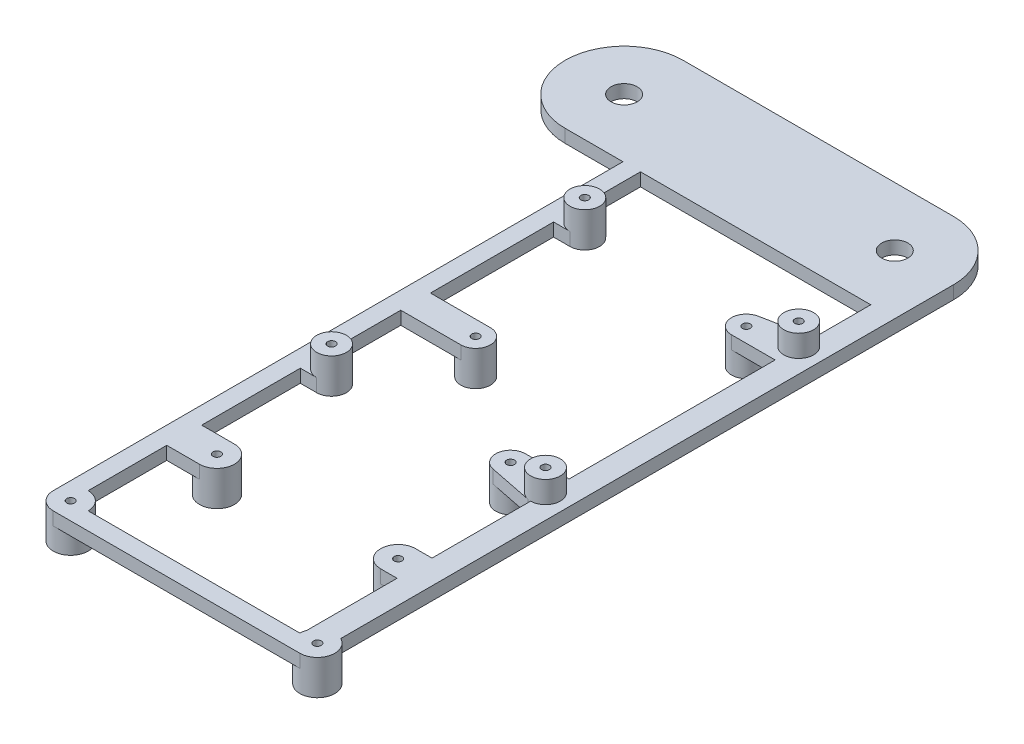
SolidWorks part; units mm, degrees
ref_plane "Front Plane" through (0, 0, 0) normal (0, 0, 1) x (1, 0, 0)
ref_plane "Top Plane" through (0, 0, 0) normal (0, 1, 0) x (1, 0, 0)
ref_plane "Right Plane" through (0, 0, 0) normal (1, 0, 0) x (0, 0, -1)
ref_plane "SHIFTER SCREW HOLE MOUNT PLANE" through (0, -50.5, 0) normal (0, 1, 0) x (1, 0, 0)
sketch "SHIFTER SCREW HOLE LOCATIONS" plane through (0, -50.5, 0) normal (0, 1, 0) x (1, 0, 0)
  point P0 (12, 93)
  point P1 (-50, 93)
sketch "Sketch2" plane through (0, -50.5, 0) normal (0, 1, 0) x (1, 0, 0)
  line L0 (-50, 93) -> (12, 93) construction
  line L1 (-50, 106.5) -> (12, 106.5)
  line L2 (-50, 79.5) -> (12, 79.5)
  arc A0 (-50, 106.5) -> (-50, 79.5) centre (-50, 93) ccw
  arc A1 (12, 79.5) -> (12, 106.5) centre (12, 93) ccw
  circle A2 centre (-50, 93) radius 3
  circle A3 centre (12, 93) radius 3
  point P4 (-19, 93)
  point P15 (0, 0)
  point P16 (0, 0)
  point P17 (0, 0)
  dimension "D1" = 13.5
  dimension "D2" = 6
extrude "SHIFTER HOLE IF" add sketch "Sketch2" against normal blind 3
sketch "Sketch3" plane through (0, -50.5, 0) normal (0, 1, 0) x (1, 0, 0)
  line L1 (-29, 63) -> (20, 63) construction
  line L2 (-29, 63) -> (-29, 5) construction
  line L3 (-29, 5) -> (20, 5) construction
  line L4 (20, 63) -> (20, 5) construction
  circle A0 centre (-29, 63) radius 0.9
  circle A1 centre (20, 63) radius 0.9
  circle A2 centre (20, 5) radius 0.9
  circle A3 centre (-29, 5) radius 0.9
  circle A4 centre (-29, 63) radius 3.4
  circle A5 centre (20, 63) radius 3.4
  circle A6 centre (20, 5) radius 3.4
  circle A7 centre (-29, 5) radius 3.4
  point P1 (10.7793, 10)
  point P16 (-8.0489, -3.7251)
  point P18 (-3.7899, 3.2614)
  dimension "D1" = 1.8
  dimension "D2" = 49
  dimension "D3" = 58
  dimension "D5" = 20
  dimension "D6" = 5
  dimension "D4" = 2.5
extrude "RPI4 SCREW BOSSES" add sketch "Sketch3" along normal blind 5 and the other way blind 3 separate body
sketch "Sketch4" plane through (0, -50.5, 0) normal (0, 1, 0) x (1, 0, 0)
  line L0 (10, 61) -> (10, 7) construction
  line L1 (20, 63) -> (20, 5) construction
  line L2 (20, 34) -> (10, 34) construction
  circle A0 centre (10, 61) radius 0.9
  circle A1 centre (10, 7) radius 0.9
  circle A2 centre (10, 61) radius 3.4
  circle A3 centre (10, 7) radius 3.4
  circle A4 centre (-19, 28) radius 0.9
  circle A5 centre (-19, 28) radius 3.4
  point P15 (8.9247, 34)
  dimension "D2" = 1.8
  dimension "D3" = 6.8
  dimension "D1" = 54
  dimension "D4" = 29
  dimension "D5" = 21
  dimension "D6" = 10
extrude "CAN SWITCH SCREW BOSSES" add sketch "Sketch4" against normal blind 8 separate body
sketch "Sketch5" plane through (0, -50.5, 0) normal (0, 1, 0) x (1, 0, 0)
  line L0 (-25.25, -25) -> (16.25, -25) construction
  line L1 (-32.75, -51) -> (23.75, -51) construction
  line L2 (-4.5, -51) -> (-4.5, -25) construction
  line L3 (-29, 5) -> (20, 5) construction
  line L4 (-4.5, -25) -> (-4.5, 5) construction
  circle A0 centre (-25.25, -25) radius 0.9
  circle A1 centre (-32.75, -51) radius 0.9
  circle A2 centre (16.25, -25) radius 0.9
  circle A3 centre (23.75, -51) radius 0.9
  circle A4 centre (-32.75, -51) radius 4
  circle A5 centre (-25.25, -25) radius 4
  circle A6 centre (16.25, -25) radius 4
  circle A7 centre (23.75, -51) radius 4
  dimension "D4" = 1.8
  dimension "D6" = 30
  dimension "D5" = 8
  dimension "D1" = 41.5
  dimension "D2" = 26
  dimension "D3" = 56.5
extrude "5V REG MOUNT POSTS" add sketch "Sketch5" against normal blind 8 separate body
sketch "Sketch6" plane through (0, -50.5, 0) normal (0, 1, 0) x (1, 0, 0)
  line L0 (25.5, 93) -> (25.5, -47.4031)
  line L1 (-36.75, 79.5) -> (-36.75, -51)
  line L2 (-50, 79.5) -> (12, 79.5) construction
  line L3 (-36.75, 79.5) -> (12, 79.5)
  line L4 (-32.75, -55) -> (23.75, -55)
  arc A0 (12, 79.5) -> (12, 106.5) centre (12, 93) ccw construction
  circle A1 centre (23.75, -51) radius 4 construction
  arc A2 (23.75, -55) -> (25.5, -47.4031) centre (23.75, -51) ccw
  circle A3 centre (-32.75, -51) radius 4 construction
  arc A4 (12, 79.5) -> (25.5, 93) centre (12, 93) ccw
  arc A5 (-36.75, -51) -> (-32.75, -55) centre (-32.75, -51) ccw
  circle A6 centre (-25.25, -25) radius 0.9 construction
  circle A7 centre (16.25, -25) radius 0.9 construction
  circle A8 centre (23.75, -51) radius 0.9 construction
  circle A9 centre (-32.75, -51) radius 0.9 construction
  circle A10 centre (-25.25, -25) radius 0.9
  circle A11 centre (16.25, -25) radius 0.9
  circle A12 centre (23.75, -51) radius 0.9
  circle A13 centre (-32.75, -51) radius 0.9
  circle A14 centre (-29, 63) radius 0.9 construction
  circle A15 centre (20, 63) radius 0.9 construction
  circle A16 centre (10, 61) radius 0.9 construction
  circle A17 centre (-19, 28) radius 0.9 construction
  circle A18 centre (10, 7) radius 0.9 construction
  circle A19 centre (20, 5) radius 0.9 construction
  circle A20 centre (-29, 5) radius 0.9 construction
  circle A21 centre (-29, 63) radius 0.9
  circle A22 centre (20, 63) radius 0.9
  circle A23 centre (10, 61) radius 0.9
  circle A24 centre (-19, 28) radius 0.9
  circle A25 centre (10, 7) radius 0.9
  circle A26 centre (20, 5) radius 0.9
  circle A27 centre (-29, 5) radius 0.9
extrude "IF LINK" add sketch "Sketch6" against normal blind 3
sketch "Sketch7" plane through (0, -50.5, 0) normal (0, 1, 0) x (1, 0, 0)
  line L0 (-32.75, 66.4) -> (-32.75, 79.5)
  line L1 (-36.75, 79.5) -> (12, 79.5) construction
  line L2 (-32.75, 79.5) -> (20, 79.5)
  line L3 (20, 79.5) -> (20, 66.4)
  line L4 (19.3332, 66.334) -> (9.3332, 64.334)
  line L5 (10, 57.6) -> (20, 57.6)
  line L6 (20, 57.6) -> (20, 10.4)
  line L7 (20, 10.4) -> (10, 10.4)
  line L8 (10, 61) -> (10, 7) construction
  line L9 (9.3332, 3.666) -> (19.3332, 1.666)
  line L10 (20, 1.6) -> (20, -21)
  line L11 (20, -21) -> (16.25, -21)
  line L12 (16.25, -29) -> (20, -29)
  line L13 (20, -29) -> (20, -49.6081)
  line L14 (19.75, -51) -> (-28.75, -51)
  line L15 (-32.75, -47) -> (-32.75, -29)
  line L16 (-32.75, -29) -> (-25.25, -29)
  line L17 (-25.25, -21) -> (-32.75, -21)
  line L18 (-32.75, -21) -> (-32.75, 1.6)
  line L19 (-32.75, 1.6) -> (-29, 1.6)
  line L20 (-29, 8.4) -> (-32.75, 8.4)
  line L21 (-32.75, 8.4) -> (-32.75, 24.6)
  line L22 (-32.75, 24.6) -> (-19, 24.6)
  line L23 (-19, 31.4) -> (-32.75, 31.4)
  line L24 (-32.75, 31.4) -> (-32.75, 59.6)
  line L25 (-32.75, 59.6) -> (-29, 59.6)
  line L26 (-32.75, 66.4) -> (-29, 66.4)
  circle A0 centre (-29, 63) radius 3.4 construction
  circle A1 centre (20, 63) radius 3.4 construction
  arc A2 (20, 66.4) -> (19.3332, 66.334) centre (20, 63) ccw
  circle A3 centre (10, 61) radius 3.4 construction
  arc A4 (9.3332, 64.334) -> (10, 57.6) centre (10, 61) ccw
  circle A5 centre (10, 7) radius 3.4 construction
  arc A6 (10, 10.4) -> (9.3332, 3.666) centre (10, 7) ccw
  circle A7 centre (20, 5) radius 3.4 construction
  arc A8 (19.3332, 1.666) -> (20, 1.6) centre (20, 5) ccw
  circle A9 centre (16.25, -25) radius 4 construction
  arc A10 (16.25, -21) -> (16.25, -29) centre (16.25, -25) ccw
  circle A11 centre (23.75, -51) radius 4 construction
  arc A12 (20, -49.6081) -> (19.75, -51) centre (23.75, -51) ccw
  circle A13 centre (-32.75, -51) radius 4 construction
  arc A14 (-28.75, -51) -> (-32.75, -47) centre (-32.75, -51) ccw
  circle A15 centre (-19, 28) radius 3.4 construction
  circle A16 centre (-25.25, -25) radius 4 construction
  circle A17 centre (-29, 5) radius 3.4 construction
  arc A18 (-29, 59.6) -> (-29, 66.4) centre (-29, 63) ccw
  arc A19 (-19, 24.6) -> (-19, 31.4) centre (-19, 28) ccw
  arc A20 (-25.25, -29) -> (-25.25, -21) centre (-25.25, -25) ccw
  arc A21 (-29, 1.6) -> (-29, 8.4) centre (-29, 5) ccw
extrude "Cut-Extrude1" cut sketch "Sketch7" against normal through all both and the other way through all
